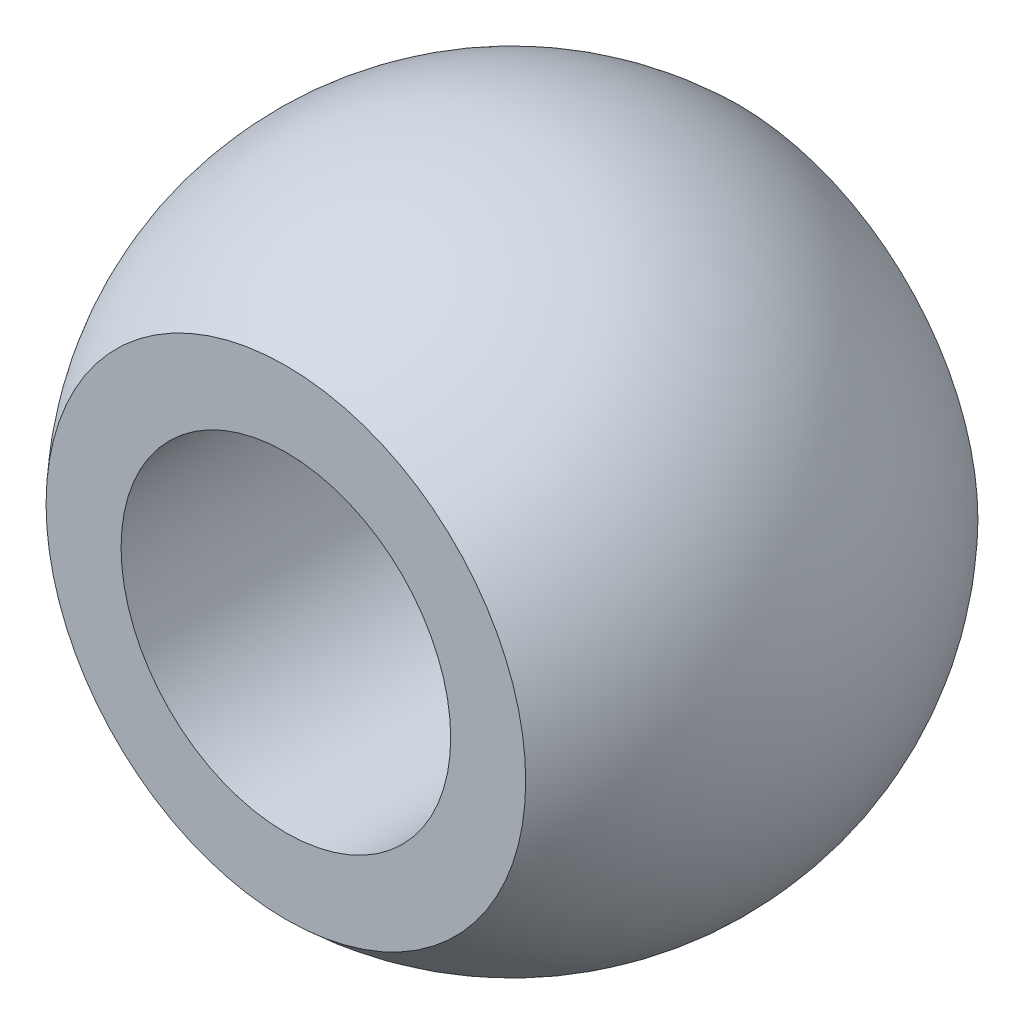
SolidWorks part; units mm, degrees
ref_plane "Front" through (0, 0, 0) normal (0, 0, 1) x (1, 0, 0)
ref_plane "Top" through (0, 0, 0) normal (0, 1, 0) x (1, 0, 0)
ref_plane "Right" through (0, 0, 0) normal (1, 0, 0) x (0, 0, -1)
sketch "Sketch1" plane through (0, 0, 0) normal (0, 0, 1) x (1, 0, 0)
  circle A0 centre (0, 0) radius 3.175 construction
  circle A1 centre (0, 0) radius 6.35 construction
  circle A2 centre (0, 0) radius 6.4135 construction
  circle A3 centre (0, 0) radius 8.3337
  dimension "D1" = 12.827
  dimension "D OD" = 16.6675
  dimension "B Hole Dia" = 6.35
  dimension "Ball Dia" = 12.7
extrude "Extrude1" add sketch "Sketch1" along normal mid plane 6.35
sketch "Sketch2" plane through (0, 0, 0) normal (0, 0, 1) x (1, 0, 0)
  line L0 (0, 6.4135) -> (0, -6.4135)
  line L1 (0, 6.4135) -> (0, 8.3337) construction
  circle A0 centre (0, 0) radius 6.4135 construction
  arc A1 (0, -6.4135) -> (0, 6.4135) centre (0, 0) ccw
  circle A2 centre (0, 0) radius 8.3337 construction
revolve "Cut-Revolve1" cut sketch "Sketch2" angle 360 about L1
sketch "Sketch3" plane through (0, 0, 0) normal (0, 0, 1) x (1, 0, 0)
  line L0 (0, 6.35) -> (0, -6.35)
  line L1 (0, 6.35) -> (0, 8.3337) construction
  circle A0 centre (0, 0) radius 6.35 construction
  arc A1 (0, -6.35) -> (0, 6.35) centre (0, 0) ccw
  circle A2 centre (0, 0) radius 8.3337 construction
revolve "Revolve1" add sketch "Sketch3" angle 360 about L1
sketch "Sketch4" plane through (0, 0, 0) normal (0, 0, 1) x (1, 0, 0)
  circle A0 centre (0, 0) radius 3.175 construction
  circle A1 centre (0, 0) radius 3.175
extrude "Cut-Extrude1" cut sketch "Sketch4" against normal through all and the other way through all
sketch "Sketch5" plane through (0, 0, 0) normal (1, 0, 0) x (0, 0, -1)
  line L0 (-4.3561, 8.3337) -> (4.3561, 8.3337) construction
  line L1 (-4.3561, 8.3337) -> (-5.4993, 8.3337)
  line L2 (-4.3561, 8.3337) -> (-4.3561, -8.3337)
  line L3 (-4.3561, -8.3337) -> (-5.4993, -8.3337)
  line L4 (-5.4993, 8.3337) -> (-5.4993, -8.3337)
  line L5 (4.3561, -8.3337) -> (5.4993, -8.3337)
  line L6 (4.3561, -8.3337) -> (4.3561, 8.3337)
  line L7 (4.3561, 8.3337) -> (5.4993, 8.3337)
  line L8 (5.4993, -8.3337) -> (5.4993, 8.3337)
  line L16 (3.175, 8.3337) -> (-3.175, 8.3337) construction
  line L17 (5.4993, -3.175) -> (5.4993, 3.175) construction
  line L18 (-5.4993, -3.175) -> (-5.4993, 3.175) construction
  line L19 (-4.3561, -8.3337) -> (4.3561, -8.3337) construction
  line L20 (-3.175, -8.3337) -> (3.175, -8.3337) construction
  line L21 (0, 0) -> (-4.3561, 1.0458) construction
  line L22 (0, 0) -> (-4.3561, -1.0458) construction
  dimension "W ball Width" = 8.7122
  dimension "Mis Angle" = 27
extrude "Cut-Extrude2" cut sketch "Sketch5" against normal through all and the other way through all
chamfer "Chamfer1" distance 0.5588 angle 45 2 edges at (8.3337, 0, 3.175) (8.3337, 0, -3.175)
sketch "Sketch7" plane through (0, 0, 0) normal (1, 0, 0) x (0, 0, -1)
  line L0 (0, 0) -> (-4.3561, -1.0458) construction
  line L1 (0, 0) -> (-4.3561, 1.0458) construction
  line L2 (0, 0) -> (-4.3561, -1.0458) construction
  line L3 (0, 0) -> (-4.3561, 1.0458) construction
sketch "Sketch8" plane through (0, 0, 0) normal (1, 0, 0) x (0, 0, -1)
  line L0 (-0.8496, 8.3337) -> (-0.4801, 7.6937)
  line L1 (-0.4801, 7.6937) -> (0.4801, 7.6937)
  line L2 (0.4801, 7.6937) -> (0.8496, 8.3337)
  line L3 (-0.8496, 8.3337) -> (0.8496, 8.3337)
  line L4 (2.6162, 8.3337) -> (-2.6162, 8.3337) construction
  line L5 (0, 0) -> (0, 7.6937) construction
  line L6 (0, 0) -> (4.3561, 0) construction
  line L7 (4.3561, -4.6203) -> (4.3561, 4.6203) construction
  line L8 (0, 6.4135) -> (0, 8.3337) construction
  arc A0 (3.175, 5.5725) -> (-3.175, 5.5725) centre (0, 0) ccw construction
  dimension "D1" = 60
  dimension "D2" = 1.9202
  dimension "D3" = 0.6401
  dimension "D4" = 0.9601
revolve "Cut-Revolve2" cut sketch "Sketch8" angle 360 about L6
delete or keep bodies "Body-Delete/Keep 1" type delete bodies bodies 113
ref_point "Point1"
equation "\"D1@Sketch1\"=\"Ball Dia@Sketch1\"*1.01"
equation "\"D3@Sketch8\" = \"D2@Sketch8\"/3"
equation "\"D4@Sketch8\" = \"D3@Sketch8\"*1.5"
